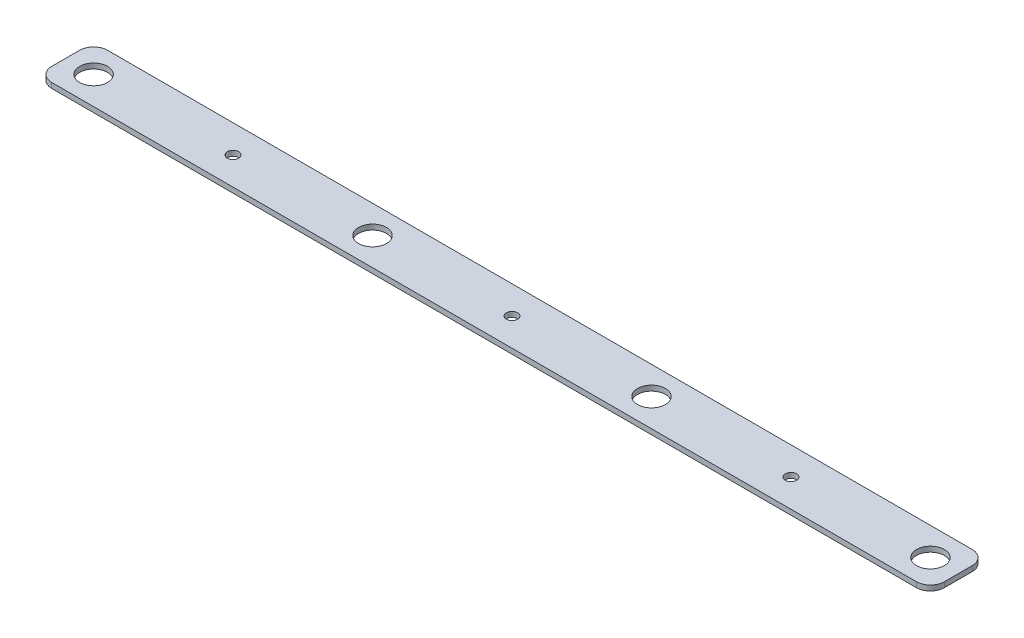
SolidWorks part; units mm, degrees
ref_plane "Front Plane" through (0, 0, 0) normal (0, 0, 1) x (1, 0, 0)
ref_plane "Top Plane" through (0, 0, 0) normal (0, 1, 0) x (1, 0, 0)
ref_plane "Right Plane" through (0, 0, 0) normal (1, 0, 0) x (0, 0, -1)
sketch "Sketch1" plane through (0, 0, 0) normal (0, 1, 0) x (1, 0, 0)
  line L0 (12.7, 12.7) -> (139.7, 12.7) construction
  line L1 (0, 0) -> (406.4, 0)
  line L2 (0, 0) -> (0, 25.4)
  line L3 (0, 25.4) -> (406.4, 25.4)
  line L4 (406.4, 0) -> (406.4, 25.4)
  line L5 (139.7, 12.7) -> (266.7, 12.7) construction
  line L6 (266.7, 12.7) -> (393.7, 12.7) construction
  circle A0 centre (12.7, 12.7) radius 6.35
  circle A1 centre (393.7, 12.7) radius 6.35
  circle A2 centre (139.7, 12.7) radius 6.35
  circle A3 centre (266.7, 12.7) radius 6.35
  circle A4 centre (76.2, 12.7) radius 2.5797
  circle A5 centre (203.2, 12.7) radius 2.5797
  circle A6 centre (330.2, 12.7) radius 2.5797
  dimension "D3" = 12.7
  dimension "D8" = 5.1594
  dimension "D1" = 406.4
  dimension "D2" = 25.4
  dimension "D4" = 12.7
  dimension "D5" = 12.7
  dimension "D6" = 12.7
  dimension "D7" = 12.7
extrude "Boss-Extrude1" add sketch "Sketch1" along normal blind 2.3813
fillet "Fillet1" radius 6.35 4 edges at (406.4, 1.1906, 0) (406.4, 1.1906, -25.4) (0, 1.1906, -25.4) (0, 1.1906, 0)
equation "\"D6@Sketch1\"=\"D5@Sketch1\""
equation "\"D7@Sketch1\"=\"D4@Sketch1\""
